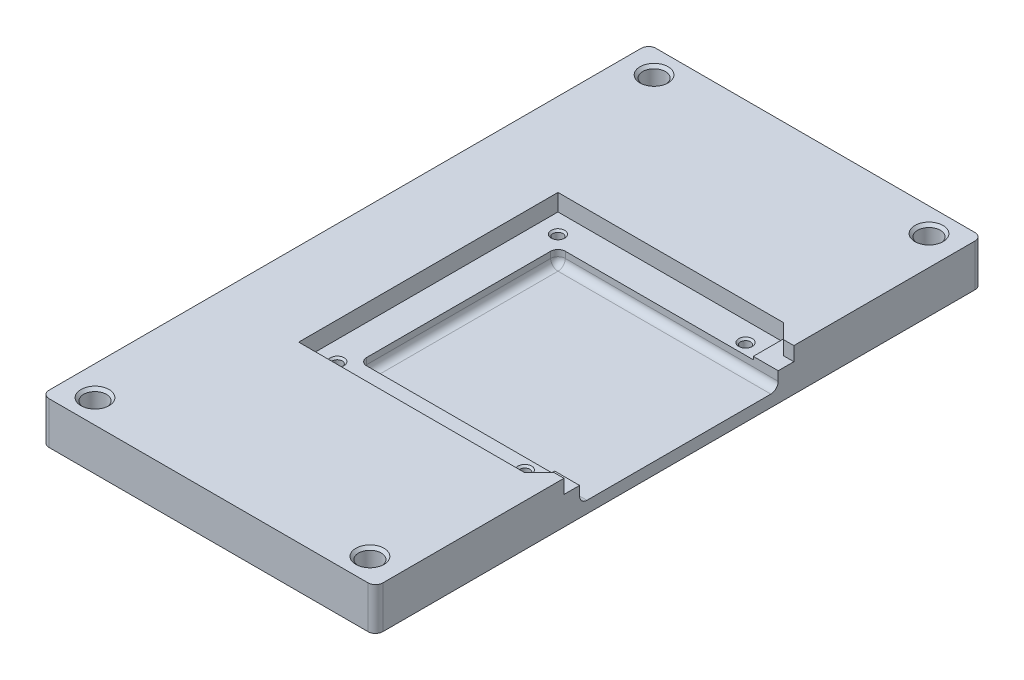
SolidWorks part; units mm, degrees
ref_plane "Front Plane" through (0, 0, 0) normal (0, 0, 1) x (1, 0, 0)
ref_plane "Top Plane" through (0, 0, 0) normal (0, 1, 0) x (1, 0, 0)
ref_plane "Right Plane" through (0, 0, 0) normal (1, 0, 0) x (0, 0, -1)
sketch "Sketch1" plane through (0, 0, 0) normal (0, 1, 0) x (1, 0, 0)
  line L0 (0, -67.5) -> (0, 67.5) construction
  line L1 (45.375, 67.5) -> (-45.375, 67.5) construction
  line L2 (-45.375, 67.5) -> (-45.375, -67.5)
  line L3 (-45.375, 0) -> (45.375, 0) construction
  line L4 (-45.375, 67.5) -> (-45.375, 80.5)
  line L5 (-43.375, 82.5) -> (43.375, 82.5)
  line L6 (0, 82.5) -> (0, 67.5) construction
  line L7 (45.375, 67.5) -> (45.375, 80.5)
  line L8 (45.375, 67.5) -> (45.375, -67.5)
  line L9 (0, -82.5) -> (0, -67.5) construction
  line L10 (45.375, -67.5) -> (-45.375, -67.5) construction
  line L11 (45.375, -67.5) -> (45.375, -80.5)
  line L12 (-43.375, -82.5) -> (43.375, -82.5)
  line L13 (-45.375, -67.5) -> (-45.375, -80.5)
  line L14 (-45.375, 70.5) -> (45.375, 70.5) construction
  circle A1 centre (-37.375, 76) radius 3.075 construction
  circle A2 centre (37.375, 76) radius 3.075 construction
  circle A5 centre (37.375, -76) radius 3.075 construction
  circle A6 centre (-37.375, -76) radius 3.075 construction
  arc A8 (-43.375, -82.5) -> (-45.375, -80.5) centre (-43.375, -80.5) cw
  arc A9 (45.375, -80.5) -> (43.375, -82.5) centre (43.375, -80.5) cw
  arc A10 (45.375, 80.5) -> (43.375, 82.5) centre (43.375, 80.5) ccw
  arc A11 (-45.375, 80.5) -> (-43.375, 82.5) centre (-43.375, 80.5) cw
  point P24 (0, 0)
  point P36 (-45.375, -82.5)
  point P39 (45.375, -82.5)
  point P42 (45.375, 82.5)
  point P45 (-45.375, 82.5)
  dimension "D10" = 2
  dimension "D3" = 6.15
  dimension "D1" = 45.375
  dimension "D2" = 67.5
  dimension "D4" = 6.5
  dimension "D6" = 8
  dimension "D7" = 8.5
  dimension "D8" = 12
  dimension "D9" = 3
  dimension "D11" = 82.5
extrude "Boss-Extrude1" add sketch "Sketch1" along normal blind 11.5
sketch "Sketch3" plane through (0, 11.5, 0) normal (0, 1, 0) x (1, 0, 0)
  line L0 (0, 0) -> (-45.375, 0) construction
  line L1 (-45.375, 80.5) -> (-45.375, -80.5) construction
  line L2 (0, 0) -> (0, 82.5) construction
  line L3 (43.375, 82.5) -> (-43.375, 82.5) construction
  line L4 (3.96, -16.3) -> (3.96, 16.3)
  line L5 (-2.46, -17.8) -> (2.46, -17.8)
  line L6 (-3.96, 16.3) -> (-3.96, -16.3)
  line L7 (2.46, 17.8) -> (-2.46, 17.8)
  line L8 (0, 17.8) -> (0, -17.8) construction
  line L9 (13.25, 0) -> (0, 0) construction
  line L10 (16.15, 10.025) -> (10.35, 10.025)
  line L11 (16.15, 10.025) -> (16.15, -10.025)
  line L12 (16.15, -10.025) -> (10.35, -10.025)
  line L13 (10.35, 10.025) -> (10.35, -10.025)
  line L14 (16.15, 10.025) -> (10.35, -10.025) construction
  line L15 (16.15, -10.025) -> (10.35, 10.025) construction
  line L16 (13.25, 0) -> (13.25, 10.025) construction
  line L17 (-16.15, 10.025) -> (-16.15, -10.025)
  line L18 (-16.15, -10.025) -> (-10.35, -10.025)
  line L23 (-16.15, 10.025) -> (-10.35, 10.025)
  line L24 (-10.35, 10.025) -> (-10.35, -10.025)
  arc A0 (-2.46, 17.8) -> (-3.96, 16.3) centre (-2.46, 16.3) ccw
  arc A1 (3.96, 16.3) -> (2.46, 17.8) centre (2.46, 16.3) ccw
  arc A2 (2.46, -17.8) -> (3.96, -16.3) centre (2.46, -16.3) ccw
  arc A3 (-3.96, -16.3) -> (-2.46, -17.8) centre (-2.46, -16.3) ccw
  point P9 (0, 0)
  point P23 (0, 0)
  dimension "D2" = 1.5
  dimension "D1" = 35.6
  dimension "D3" = 7.92
  dimension "D4" = 20.05
  dimension "D5" = 5.8
  dimension "D6" = 13.25
sketch "Sketch4" plane through (0, 11.5, 0) normal (0, 1, 0) x (1, 0, 0)
  circle A0 centre (-37.375, -76) radius 3.075 construction
  circle A1 centre (37.375, -76) radius 3.075 construction
  circle A2 centre (37.375, 76) radius 3.075 construction
  circle A5 centre (-37.375, 76) radius 3.075 construction
  circle A8 centre (-37.375, -76) radius 3.075
  circle A9 centre (37.375, -76) radius 3.075
  circle A10 centre (37.375, 76) radius 3.075
  circle A13 centre (-37.375, 76) radius 3.075
extrude "Cut-Extrude1" cut sketch "Sketch4" against normal blind 6
sketch "Sketch21" plane through (0, 11.5, 0) normal (0, 1, 0) x (1, 0, 0)
  line L0 (38.5, 35) -> (-22.5, 35) construction
  line L1 (38.5, 35) -> (42.5, 31) construction
  line L2 (-22.5, 35) -> (-22.5, -35) construction
  line L3 (-22.5, 0) -> (0, 0) construction
  line L4 (0, 0) -> (38.5, 0) construction
  line L5 (38.5, -35) -> (38.5, 35) construction
  line L6 (38.5, -35) -> (-22.5, -35) construction
  line L7 (42.5, 31) -> (45.375, 31) construction
  line L8 (45.375, -80.5) -> (45.375, 80.5) construction
  line L9 (45.375, 31) -> (45.375, -31)
  line L10 (45.375, 0) -> (38.5, 0) construction
  line L11 (42.5, -31) -> (45.375, -31) construction
  line L12 (38.5, -35) -> (42.5, -31) construction
  line L13 (42.6036, 31.25) -> (45.375, 31.25)
  line L14 (38.6036, 35.25) -> (42.6036, 31.25)
  line L15 (38.6036, 35.25) -> (-22.75, 35.25)
  line L16 (-22.75, 35.25) -> (-22.75, -35.25)
  line L17 (38.6036, -35.25) -> (-22.75, -35.25)
  line L18 (38.6036, -35.25) -> (42.6036, -31.25)
  line L19 (42.6036, -31.25) -> (45.375, -31.25)
  line L20 (45.375, -31.25) -> (45.375, -31)
  line L21 (45.375, 31) -> (45.375, 31.25)
  circle A0 centre (-17.5, 30) radius 1.6 construction
  circle A1 centre (33.5, 30) radius 1.6 construction
  circle A2 centre (33.5, -30) radius 1.6 construction
  circle A3 centre (-17.5, -30) radius 1.6 construction
  dimension "D8" = 3.2
  dimension "D1" = 22.5
  dimension "D2" = 61
  dimension "D3" = 35
  dimension "D4" = 5
  dimension "D5" = 5
  dimension "D6" = 5
  dimension "D7" = 5
  dimension "D9" = 45
  dimension "D10" = 4
  dimension "D12" = 4
  dimension "D11" = 0.25
extrude "Cut-Extrude6" cut sketch "Sketch21" against normal blind 4.6
sketch "Sketch24" plane through (0, 6.9, 0) normal (0, 1, 0) x (1, 0, 0)
  line L0 (45.375, 27) -> (-14.5, 27)
  line L2 (-14.5, 27) -> (-14.5, -27)
  line L3 (-14.5, -27) -> (45.375, -27)
  line L4 (45.375, -27) -> (45.375, 27)
  line L8 (38.5, 35) -> (-22.5, 35) construction
  line L10 (-22.5, 35) -> (-22.5, -35) construction
  line L11 (38.5, -35) -> (-22.5, -35) construction
  line L12 (45.375, -31.25) -> (45.375, 31.25) construction
  dimension "D1" = 8
  dimension "D2" = 8
  dimension "D3" = 8
extrude "Cut-Extrude3" cut sketch "Sketch24" against normal blind 3.7 and the other way through all
sketch "Sketch25" plane through (0, 6.9, 0) normal (0, 1, 0) x (1, 0, 0)
  circle A0 centre (33.5, 30) radius 1.35
  circle A1 centre (-17.5, 30) radius 1.35
  circle A2 centre (33.5, -30) radius 1.35
  circle A3 centre (-17.5, -30) radius 1.35
  dimension "D1" = 2.7
extrude "Cut-Extrude4" cut sketch "Sketch25" against normal blind 5
chamfer "Chamfer4" distance 0.5 angle 45 4 edges at (-17.5, 6.9, 31.35) (33.5, 6.9, 31.35) (33.5, 6.9, -28.65) (-17.5, 6.9, -28.65)
fillet "Fillet1" radius 2 5 edges at (15.4375, 3.2, 27) (-14.5, 5.05, 27) (-14.5, 5.05, -27) (-14.5, 3.2, 0) (15.4375, 3.2, -27)
sketch "Sketch26" plane through (0, 6.9, 0) normal (0, 1, 0) x (1, 0, 0)
  line L0 (0, 0) -> (45.375, 0) construction
  line L1 (45.375, -25) -> (45.375, 25) construction
  line L2 (38.6036, 35.25) -> (38.6036, 27)
  line L3 (45.375, 27) -> (-12.5, 27) construction
  line L4 (38.6036, 27) -> (45.375, 27)
  line L5 (45.375, 27) -> (45.375, 31.25)
  line L6 (45.375, 31.25) -> (42.6036, 31.25)
  line L7 (42.6036, 31.25) -> (38.6036, 35.25)
  line L8 (42.6036, -31.25) -> (38.6036, -35.25)
  line L9 (45.375, -31.25) -> (42.6036, -31.25)
  line L10 (45.375, -27) -> (45.375, -31.25)
  line L11 (38.6036, -27) -> (45.375, -27)
  line L12 (38.6036, -35.25) -> (38.6036, -27)
extrude "Boss-Extrude2" add sketch "Sketch26" along normal blind 0.8
chamfer "Chamfer5" distance 0.75 angle 45 4 edges at (-37.375, 11.5, 79.075) (37.375, 11.5, 79.075) (37.375, 11.5, -72.925) (-37.375, 11.5, -72.925)
equation "\"D5@Sketch21\"=\"D4@Sketch21\""
equation "\"D6@Sketch21\"=\"D4@Sketch21\""
equation "\"D7@Sketch21\"=\"D4@Sketch21\""
equation "\"D2@Sketch24\"=\"D1@Sketch24\""
equation "\"D3@Sketch24\"=\"D1@Sketch24\""
